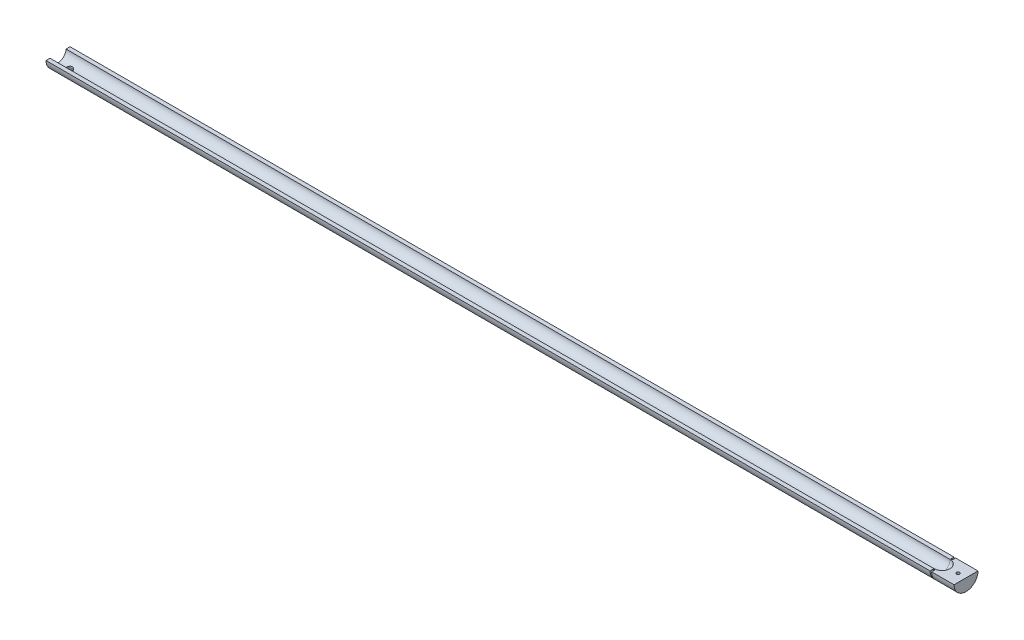
SolidWorks part; units mm, degrees
ref_plane "Front Plane" through (0, 0, 0) normal (0, 0, 1) x (1, 0, 0)
ref_plane "Top Plane" through (0, 0, 0) normal (0, 1, 0) x (1, 0, 0)
ref_plane "Right Plane" through (0, 0, 0) normal (1, 0, 0) x (0, 0, -1)
sketch "Sketch1" plane through (0, 0, 0) normal (0, 1, 0) x (1, 0, 0)
  line L1 (0, 0) -> (1803.4, 0)
  line L2 (0, 0) -> (0, 57.15)
  line L3 (0, 57.15) -> (1803.4, 57.15)
  line L4 (1803.4, 0) -> (1803.4, 57.15)
  dimension "D1" = 1803.4
  dimension "D2" = 57.15
extrude "wood block" add sketch "Sketch1" along normal blind 28.575
ref_plane "Plane1" through (0, 0, -28.575) normal (0, 0, 1) x (1, 0, 0)
sketch "Sketch2" plane through (0, 0, -28.575) normal (0, 0, 1) x (1, 0, 0)
  line L0 (1771.65, 28.575) -> (-15.875, 28.575)
  line L1 (0, 28.575) -> (1803.4, 28.575) construction
  line L2 (0, 12.7) -> (1755.775, 12.7)
  line L4 (1803.4, 28.575) -> (1803.4, 0) construction
  line L5 (0, 28.575) -> (0, 0) construction
  arc A0 (-15.875, 28.575) -> (0, 12.7) centre (0, 28.575) ccw
  arc A1 (1755.775, 12.7) -> (1771.65, 28.575) centre (1755.775, 28.575) ccw
  point P10 (0, 12.7)
  dimension "D1" = 15.875
  dimension "extralength" = 31.75
revolve "inner bore" cut sketch "Sketch2" angle 360 about L0
ref_axis "Axis1" through (0, 28.575, -28.575) along (1, 0, 0)
sketch "Sketch5" plane through (0, 0, 0) normal (0, 1, 0) x (1, 0, 0)
  line L0 (-55, 28.575) -> (55, 28.575) construction
  line L2 (15.875, 28.575) -> (0, 28.575) construction
  line L3 (0, 44.45) -> (0, 12.7) construction
  circle A0 centre (22.225, 28.575) radius 6.35
  dimension "D1" = 12.7
  dimension "D2" = 15.875
extrude "mouthpiece through hole" cut sketch "Sketch5" along normal through all
sketch "Sketch6" plane through (0, 28.575, 0) normal (0, 1, 0) x (1, 0, 0)
  line L0 (1803.4, 28.575) -> (1787.525, 28.575) construction
  line L1 (1803.4, 0) -> (1803.4, 57.15) construction
  circle A1 centre (1787.525, 28.575) radius 3.175
  dimension "D1" = 6.35
  dimension "D2" = 15.875
extrude "dowel pin hole" cut sketch "Sketch6" against normal blind 15.24
sketch "Sketch8" plane through (0, 0, 0) normal (0, -1, 0) x (1, 0, 0)
  line L0 (22.225, -28.575) -> (713.359, -28.575) construction
  circle A0 centre (22.225, -28.575) radius 8.128
  circle A1 centre (713.359, -28.575) radius 8.128
  dimension "D1" = 16.256
  dimension "D2" = 691.134
extrude "Cut-Extrude1" cut sketch "Sketch8" against normal blind 10.3124
sketch "Sketch3" plane through (1803.4, 0, 0) normal (1, 0, 0) x (0, 0, -1)
  line L0 (28.575, 15.7163) -> (28.575, -15.7163) construction
  line L1 (0, 28.575) -> (57.15, 28.575) construction
  circle A0 centre (28.575, 28.575) radius 23.8125
  dimension "D1" = 47.625
extrude "outer diameter" cut sketch "Sketch3" against normal through all flip side to cut
sketch "Sketch7" plane through (0, 28.575, 0) normal (0, 1, 0) x (1, 0, 0)
  line L0 (1803.4, 4.7625) -> (0, 4.7625) construction
  line L1 (1755.775, 4.7625) -> (1758.95, 4.7625)
  line L2 (1755.775, 4.7625) -> (1755.775, 11.1125)
  line L3 (1755.775, 11.1125) -> (1758.95, 11.1125)
  line L4 (1758.95, 4.7625) -> (1758.95, 11.1125)
  line L5 (1755.775, 12.7) -> (1755.775, 4.7625) construction
  point P9 (1756.2433, 4.7625)
  dimension "D1" = 3.175
  dimension "D2" = 6.35
revolve "end length locator" cut sketch "Sketch7" angle 360 about axis through (0, 28.575, -28.575) along (1, 0, 0)
